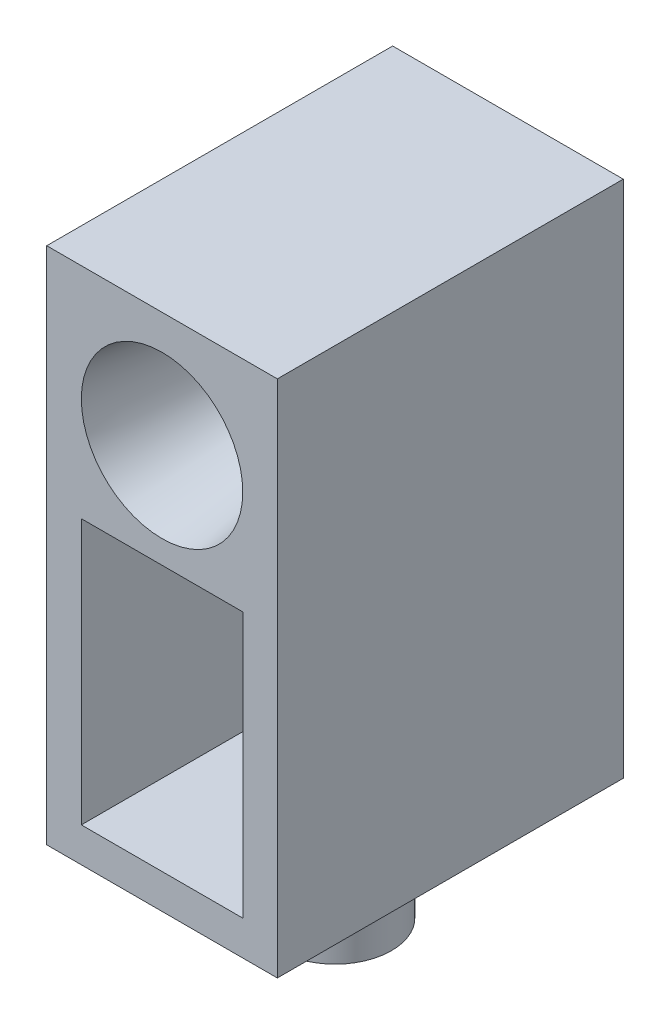
SolidWorks part; units mm, degrees
ref_plane "Front Plane" through (0, 0, 0) normal (0, 0, 1) x (1, 0, 0)
ref_plane "Top Plane" through (0, 0, 0) normal (0, 1, 0) x (1, 0, 0)
ref_plane "Right Plane" through (0, 0, 0) normal (1, 0, 0) x (0, 0, -1)
sketch "Sketch1" plane through (0, 0, 0) normal (0, 1, 0) x (1, 0, 0)
  line L1 (-10, -15) -> (10, -15)
  line L2 (-10, -15) -> (-10, 15)
  line L3 (-10, 15) -> (10, 15)
  line L4 (10, -15) -> (10, 15)
  line L5 (-10, -15) -> (10, 15) construction
  line L6 (-10, 15) -> (10, -15) construction
  point P0 (0, 0)
  dimension "D1" = 30
  dimension "D2" = 20
extrude "Boss-Extrude1" add sketch "Sketch1" along normal blind 45
sketch "Sketch2" plane through (0, 0, 0) normal (0, -1, 0) x (-1, 0, 0)
  circle A0 centre (0, 0) radius 4.9
  dimension "D1" = 9.8
extrude "Boss-Extrude2" add sketch "Sketch2" along normal blind 8
sketch "Sketch3" plane through (0, 0, 15) normal (0, 0, 1) x (1, 0, 0)
  line L0 (-10, 0) -> (10, 0) construction
  circle A0 centre (0, 35) radius 7
  dimension "D2" = 14
  dimension "D1" = 35
extrude "Cut-Extrude1" cut sketch "Sketch3" against normal blind 24 draft 9
sketch "Sketch4" plane through (0, 0, -9) normal (0, 0, 1) x (1, 0, 0)
  circle A1 centre (0, 35) radius 3.1988
extrude "Cut-Extrude2" cut sketch "Sketch4" against normal blind 3
sketch "Sketch5" plane through (0, 0, -12) normal (0, 0, 1) x (1, 0, 0)
  line L0 (-3.1988, 35) -> (3.1988, 35) construction
  circle A0 centre (0, 35) radius 3.1988 construction
  circle A1 centre (-1.5, 35) radius 0.5
  circle A2 centre (1.5, 35) radius 0.5
  circle A3 centre (0, 35) radius 3.1988 construction
  point P3 (0, 0)
  point P7 (0, 35)
  point P11 (0, 0)
  point P12 (-1.5191, 35)
  point P13 (0, 0)
  point P14 (0, 0)
  point P15 (0, 35)
  point P16 (-3.1988, 35)
  dimension "D1" = 1
  dimension "D2" = 1
  dimension "D3" = 3
  dimension "D4" = 1.5
extrude "Cut-Extrude3" cut sketch "Sketch5" against normal blind 3
sketch "Sketch6" plane through (0, 0, 15) normal (0, 0, 1) x (1, 0, 0)
  line L0 (-10, 0) -> (10, 0) construction
  line L1 (-7, 3) -> (7, 3)
  line L2 (-7, 3) -> (-7, 26)
  line L3 (-7, 26) -> (7, 26)
  line L4 (7, 3) -> (7, 26)
  line L5 (-10, 45) -> (-10, 0) construction
  line L6 (10, 45) -> (10, 0) construction
  circle A0 centre (0, 35) radius 7 construction
  dimension "D1" = 3
  dimension "D2" = 3
  dimension "D3" = 3
  dimension "D4" = 9
extrude "Cut-Extrude4" cut sketch "Sketch6" against normal through all
